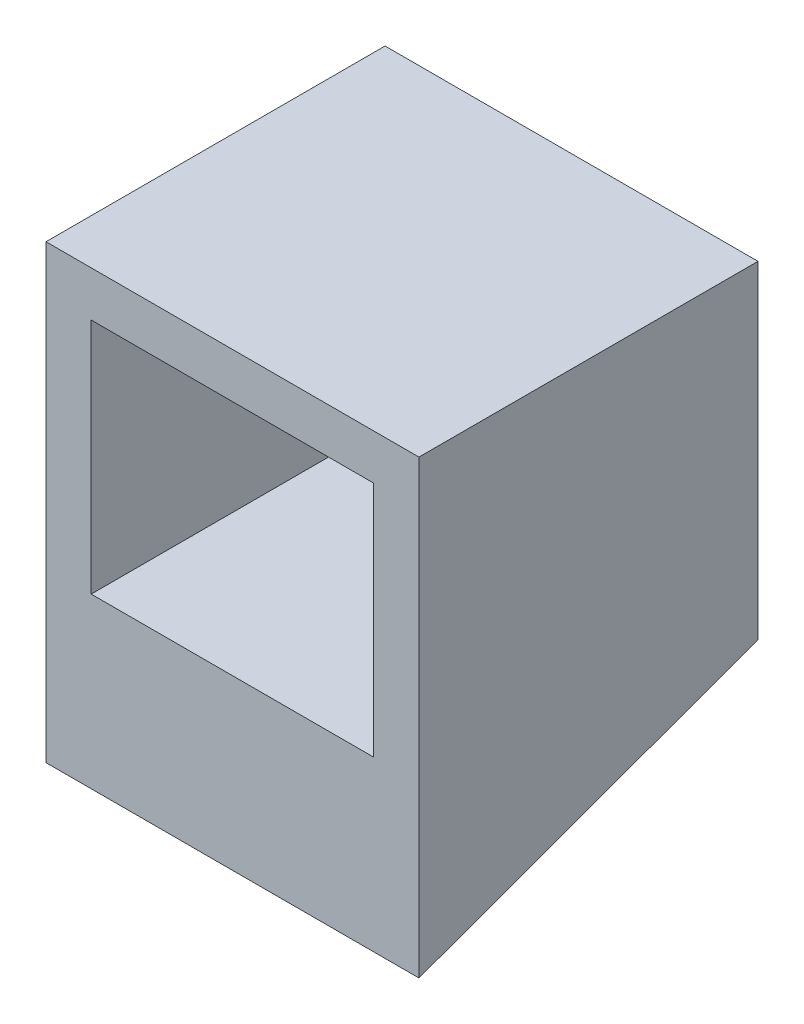
SolidWorks part; units mm, degrees
ref_plane "Front Plane" through (0, 0, 0) normal (0, 0, 1) x (1, 0, 0)
ref_plane "Top Plane" through (0, 0, 0) normal (0, 1, 0) x (1, 0, 0)
ref_plane "Right Plane" through (0, 0, 0) normal (1, 0, 0) x (0, 0, -1)
sketch "Sketch1" plane through (0, 0, 0) normal (0, 0, 1) x (1, 0, 0)
  line L0 (-2, 2) -> (-2, -12.5)
  line L1 (0, 0) -> (12.5, 0)
  line L2 (0, 0) -> (0, -10.5)
  line L3 (0, -10.5) -> (12.5, -10.5)
  line L4 (12.5, 0) -> (12.5, -10.5)
  line L5 (-2, -12.5) -> (14.5, -12.5)
  line L6 (14.5, 2) -> (14.5, -12.5)
  line L7 (-2, 2) -> (14.5, 2)
  dimension "D1" = 12.5
  dimension "D2" = 10.5
  dimension "D3" = 2
extrude "Boss-Extrude1" add sketch "Sketch1" along normal blind 15
sketch "Sketch2" plane through (-2, 0, 0) normal (-1, 0, 0) x (0, 0, 1)
  line L0 (0, -12.5) -> (15, -17.9596)
  line L1 (15, -12.5) -> (0, -12.5) construction
  line L2 (15, -12.5) -> (15, -17.9596)
  line L3 (0, -12.5) -> (15, -12.5)
  dimension "D1" = 20
extrude "Boss-Extrude2" add sketch "Sketch2" against normal blind 16.5
